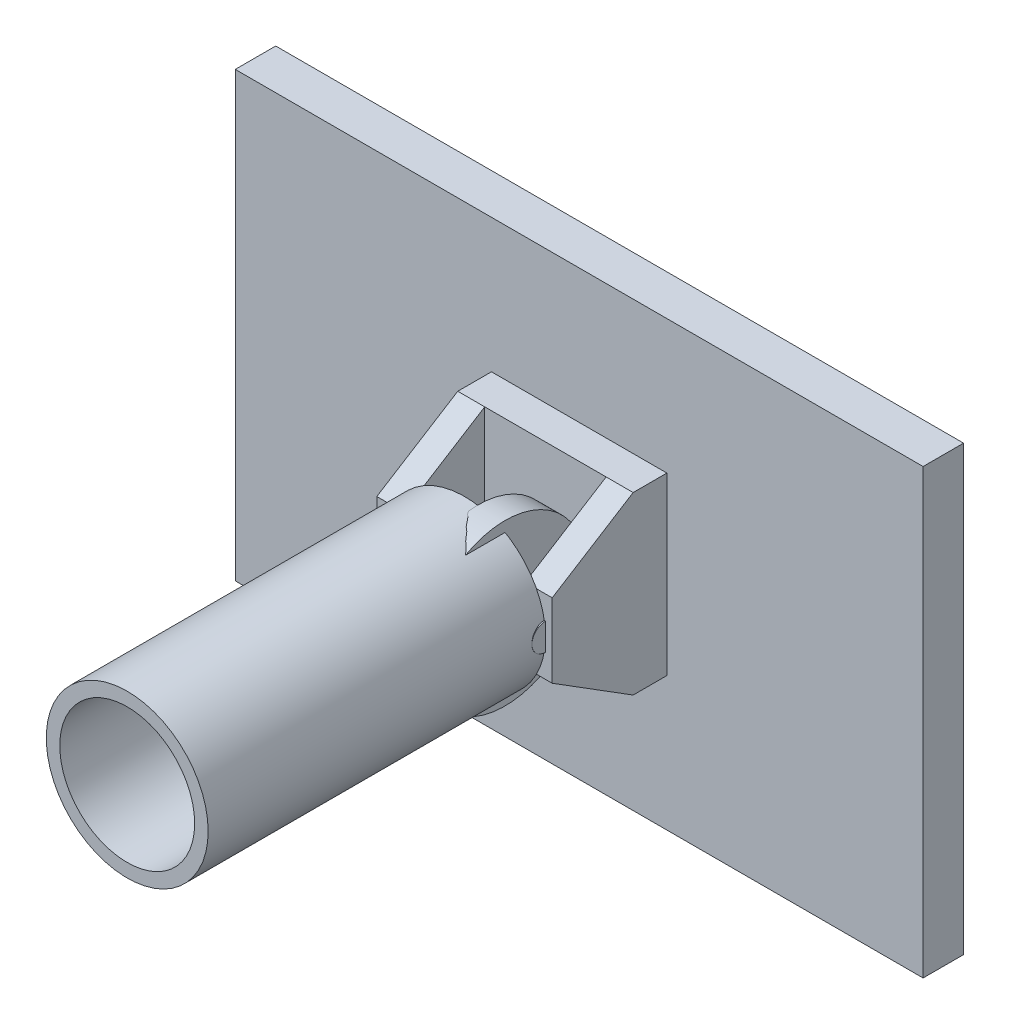
SolidWorks part; units mm, degrees
ref_plane "Front Plane" through (0, 0, 0) normal (0, 0, 1) x (1, 0, 0)
ref_plane "Top Plane" through (0, 0, 0) normal (0, 1, 0) x (1, 0, 0)
ref_plane "Right Plane" through (0, 0, 0) normal (1, 0, 0) x (0, 0, -1)
sketch "Sketch4" plane through (0, 0, 0) normal (0, 0, 1) x (1, 0, 0)
  line L1 (50.984, -32.833) -> (-50.984, -32.833)
  line L2 (50.984, -32.833) -> (50.984, 32.833)
  line L3 (50.984, 32.833) -> (-50.984, 32.833)
  line L4 (-50.984, -32.833) -> (-50.984, 32.833)
  line L5 (50.984, -32.833) -> (-50.984, 32.833) construction
  line L6 (50.984, 32.833) -> (-50.984, -32.833) construction
  point P0 (0, 0)
extrude "Boss-Extrude4" add sketch "Sketch4" along normal blind 6
sketch "Sketch5" plane through (0, 0, 6) normal (0, 0, 1) x (1, 0, 0)
  line L1 (13, -13) -> (-13, -13)
  line L2 (13, -13) -> (13, 13)
  line L3 (13, 13) -> (-13, 13)
  line L4 (-13, -13) -> (-13, 13)
  line L5 (13, -13) -> (-13, 13) construction
  line L6 (13, 13) -> (-13, -13) construction
  point P0 (0, 0)
  dimension "D1" = 26
  dimension "D2" = 26
extrude "Boss-Extrude5" add sketch "Sketch5" along normal blind 5 separate body
sketch "Sketch6" plane through (13, 0, 0) normal (1, 0, 0) x (0, 0, -1)
  line L0 (-11, -13) -> (-23, -5.487)
  line L1 (-23, -5.487) -> (-23, 5.487)
  line L2 (-23, 5.487) -> (-11, 13)
  line L3 (-11, -13) -> (-11, 13) construction
  line L4 (-11, -13) -> (-11, 13)
  dimension "D1" = 12
extrude "Boss-Extrude6" add sketch "Sketch6" against normal blind 4 contours L1 L2 L4 L0
mirror "Mirror1" about plane through (0, 0, 0) normal (1, 0, 0) of "Boss-Extrude6"
sketch "Sketch7" plane through (0, 0, 23) normal (0, 0, 1) x (1, 0, 0)
  circle A0 centre (0, 0) radius 12
  dimension "D1" = 24
extrude "Extrude-Thin1" add sketch "Sketch7" along normal blind 50 separate body thin thin type one direction reverse wall 2
sketch "Sketch8" plane through (0, 0, 11) normal (0, 0, 1) x (1, 0, 0)
  circle A0 centre (0, 0) radius 1.75
  dimension "D1" = 3.5
extrude "Boss-Extrude7" add sketch "Sketch8" along normal blind 5 separate body
sketch "Sketch10" plane through (0, 0, 0) normal (1, 0, 0) x (0, 0, -1)
  line L0 (-23, -12) -> (-23, 12) construction
  circle A0 centre (-23, 0) radius 11.91
  dimension "D1" = 23.82
extrude "Boss-Extrude8" add sketch "Sketch10" along normal blind 4 from offset 2 separate body
sketch "Sketch11" plane through (0, 0, 0) normal (1, 0, 0) x (0, 0, -1)
  line L0 (-23, -12) -> (-23, 12) construction
  circle A0 centre (-23, 0) radius 2
  dimension "D1" = 4
extrude "Boss-Extrude9" add sketch "Sketch11" along normal mid plane 24 separate body
sketch "Sketch12" plane through (6, 0, 0) normal (1, 0, 0) x (0, 0, -1)
  circle A0 centre (-23, 0) radius 5.725
  dimension "D1" = 11.45
extrude "Boss-Extrude10" [suppressed] add sketch "Sketch12" along normal blind 3.8 separate body contours A0
mirror "Mirror3" [suppressed] about plane through (0, 0, 0) normal (1, 0, 0)
sketch "Sketch13" plane through (0, 0, 6) normal (0, 0, -1) x (-1, 0, 0)
  circle A0 centre (0, 0) radius 7.5
  dimension "D1" = 15
extrude "Boss-Extrude11" add sketch "Sketch13" along normal blind 10
sketch "Sketch14" plane through (0, 0, 0) normal (1, 0, 0) x (0, 0, -1)
  circle A0 centre (-23, 0) radius 4.125
  dimension "D1" = 8.25
extrude "Boss-Extrude12" add sketch "Sketch14" against normal blind 7 from offset 1 separate body offset against normal yes
sketch "Sketch15" plane through (0, 0, -4) normal (0, 0, -1) x (-1, 0, 0)
  circle A0 centre (0, 0) radius 3.3485
extrude "Boss-Extrude13" add sketch "Sketch15" along normal blind 15
sketch "Sketch16" plane through (0, 0, 0) normal (0, 0, -1) x (-1, 0, 0)
  line L1 (-29.3945, -9.8444) -> (-16.0838, -9.8444)
  line L2 (-29.3945, -9.8444) -> (-29.3945, 9.8444)
  line L3 (-29.3945, 9.8444) -> (-16.0838, 9.8444)
  line L4 (-16.0838, -9.8444) -> (-16.0838, 9.8444)
  line L5 (-29.3945, -9.8444) -> (-16.0838, 9.8444) construction
  line L6 (-29.3945, 9.8444) -> (-16.0838, -9.8444) construction
  point P0 (-22.7391, 0)
extrude "Boss-Extrude14" add sketch "Sketch16" along normal blind 19
